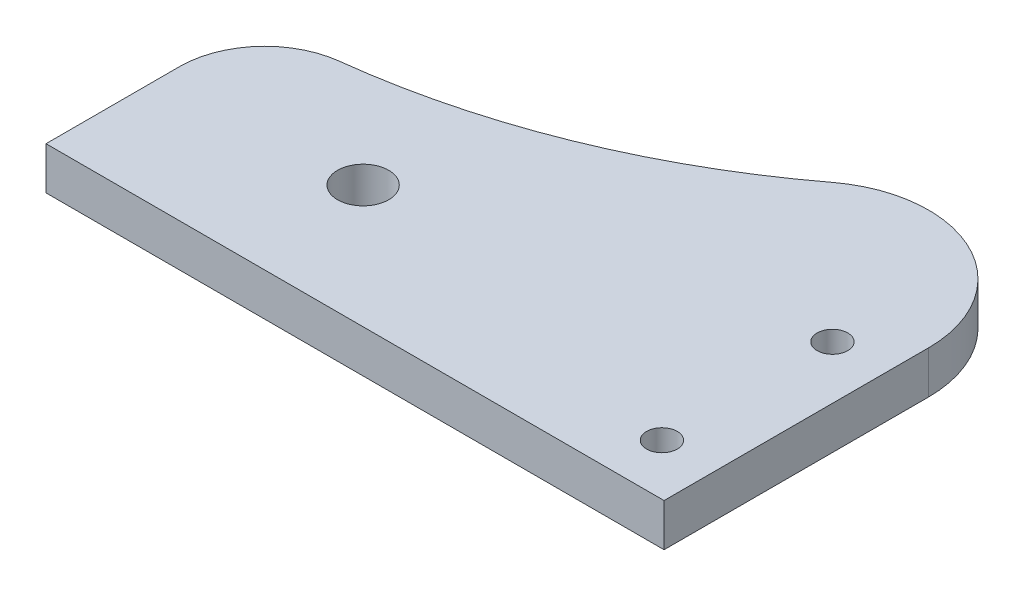
SolidWorks part; units mm, degrees
ref_plane "Front Plane" through (0, 0, 0) normal (0, 0, 1) x (1, 0, 0)
ref_plane "Top Plane" through (0, 0, 0) normal (0, 1, 0) x (1, 0, 0)
ref_plane "Right Plane" through (0, 0, 0) normal (1, 0, 0) x (0, 0, -1)
sketch "Sketch1" plane through (0, 0, 0) normal (0, 1, 0) x (1, 0, 0)
  line L0 (0, 0) -> (92.075, 0)
  line L1 (92.075, 0) -> (92.075, 85.9358)
  line L3 (0, 31.75) -> (0, 0)
  arc A1 (92.075, 85.9358) -> (0, 31.75) centre (-1.5402, 139.689) cw
  dimension "D4" = 107.95
  dimension "D1" = 31.75
  dimension "D2" = 92.075
  dimension "D3" = 85.9358
extrude "Boss-Extrude1" add sketch "Sketch1" along normal blind 6.35 contours A1 L3 L0 L1
fillet "Fillet1" radius 12.7 1 edges at (0, 3.175, -31.75)
sketch "Sketch2" plane through (0, 6.35, 0) normal (0, 1, 0) x (1, 0, 0)
  line L0 (0, 0) -> (92.075, 0) construction
  line L1 (92.075, 0) -> (92.075, 85.9358) construction
  circle A0 centre (84.1375, 7.62) radius 2.286
  circle A2 centre (84.1375, 33.02) radius 2.286
  dimension "D3" = 4.572
  dimension "D1" = 7.62
  dimension "D2" = 7.9375
  dimension "D4" = 2
extrude "Cut-Extrude1" cut sketch "Sketch2" against normal through all contours A0 | A2
sketch "Sketch3" plane through (0, 6.35, 0) normal (0, 1, 0) x (1, 0, 0)
  line L0 (0, 19.8823) -> (0, 0) construction
  line L1 (0, 0) -> (92.075, 0) construction
  circle A0 centre (28.956, 18.288) radius 3.81
  dimension "D3" = 7.62
  dimension "D1" = 28.956
  dimension "D2" = 18.288
extrude "Cut-Extrude2" cut sketch "Sketch3" against normal through all
fillet "Fillet2" radius 17.78 1 edges at (92.075, 3.175, -85.9358)
